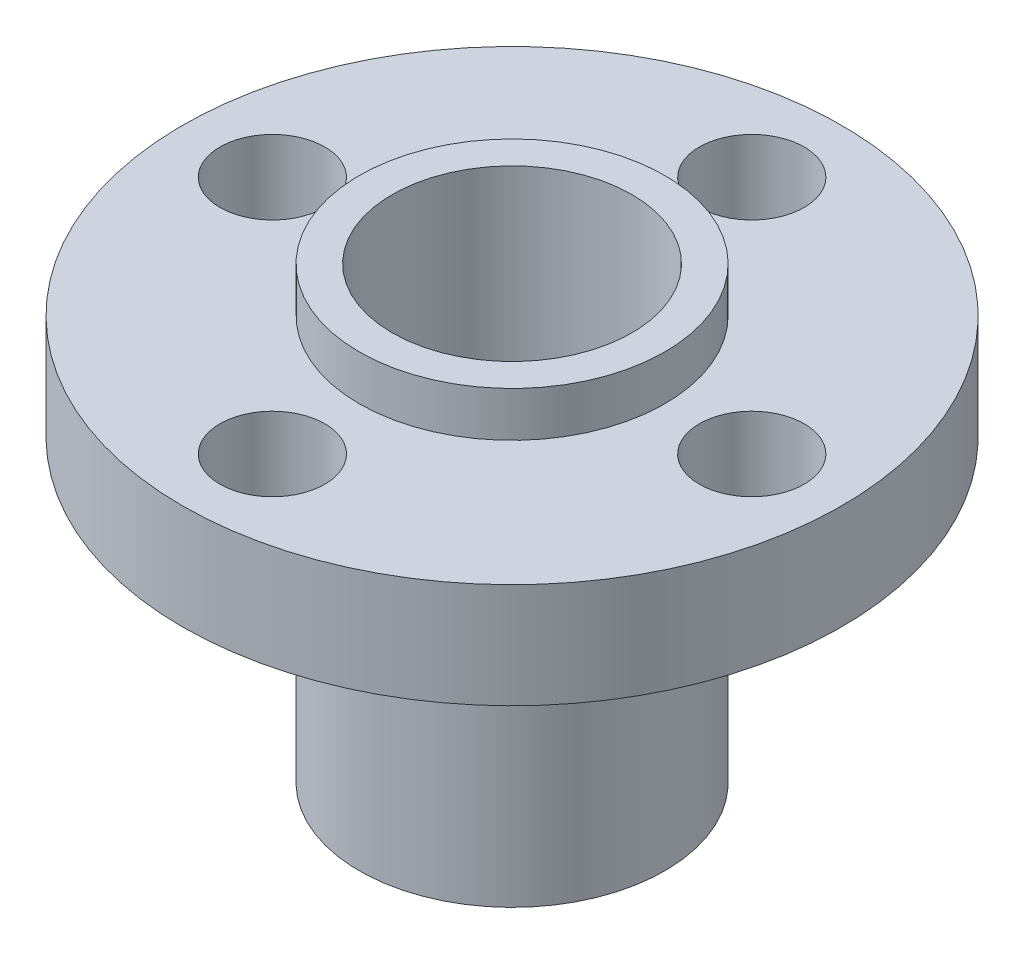
SolidWorks part; units mm, degrees
ref_plane "前视基准面" through (0, 0, 0) normal (0, 0, 1) x (1, 0, 0)
ref_plane "上视基准面" through (0, 0, 0) normal (0, 1, 0) x (1, 0, 0)
ref_plane "右视基准面" through (0, 0, 0) normal (1, 0, 0) x (0, 0, -1)
sketch "草图1" plane through (0, 0, 0) normal (0, 1, 0) x (1, 0, 0)
  circle A0 centre (0, 0) radius 11
  dimension "D1" = 22
extrude "凸台-拉伸1" add sketch "草图1" along normal blind 3.5
sketch "草图2" plane through (0, 3.5, 0) normal (0, 1, 0) x (1, 0, 0)
  circle A0 centre (0, 0) radius 5.1
  dimension "D1" = 10.2
extrude "凸台-拉伸2" add sketch "草图2" along normal blind 1.5
sketch "草图3" plane through (0, 0, 0) normal (0, -1, 0) x (1, 0, 0)
  circle A0 centre (0, 0) radius 5.1
  dimension "D1" = 10.2
extrude "凸台-拉伸3" add sketch "草图3" along normal blind 10
hole_wizard "孔1" positions "草图4" profile "草图5" legacy end condition up to next
sketch "草图4" plane through (0, 5, 0) normal (0, 1, 0) x (1, 0, 0)
  point P0 (0, 0)
sketch "草图5" plane through (0, 5, 0) normal (1, 0, 0) x (0, 0, 1)
  line L0 (0, 0) -> (0, 15)
  line L1 (0, 15) -> (4, 15)
  line L2 (4, 15) -> (4, 0)
  line L3 (4, 0) -> (0, 0)
  line L4 (0, 110) -> (0, -10) construction
  dimension "直径" = 8
  dimension "深度" = 15
sketch "草图6" plane through (0, 3.5, 0) normal (0, 1, 0) x (1, 0, 0)
  circle A0 centre (0, 0) radius 8
  dimension "D1" = 16
sketch "草图7" plane through (0, 3.5, 0) normal (0, 1, 0) x (1, 0, 0)
  circle A0 centre (0, 0) radius 8 construction
  point P0 (-8, 0)
  point P4 (0, 8)
  point P6 (8, 0)
  point P8 (0, -8)
hole_wizard "孔2" positions "草图7" profile "草图8" legacy end condition up to next
sketch "草图8" plane through (-8, 3.5, 0) normal (1, 0, 0) x (0, 0, 1)
  line L0 (0, 0) -> (0, 3.5)
  line L1 (0, 3.5) -> (1.75, 3.5)
  line L2 (1.75, 3.5) -> (1.75, 0)
  line L3 (1.75, 0) -> (0, 0)
  line L4 (0, 110) -> (0, -10) construction
  dimension "直径" = 3.5
  dimension "深度" = 3.5
